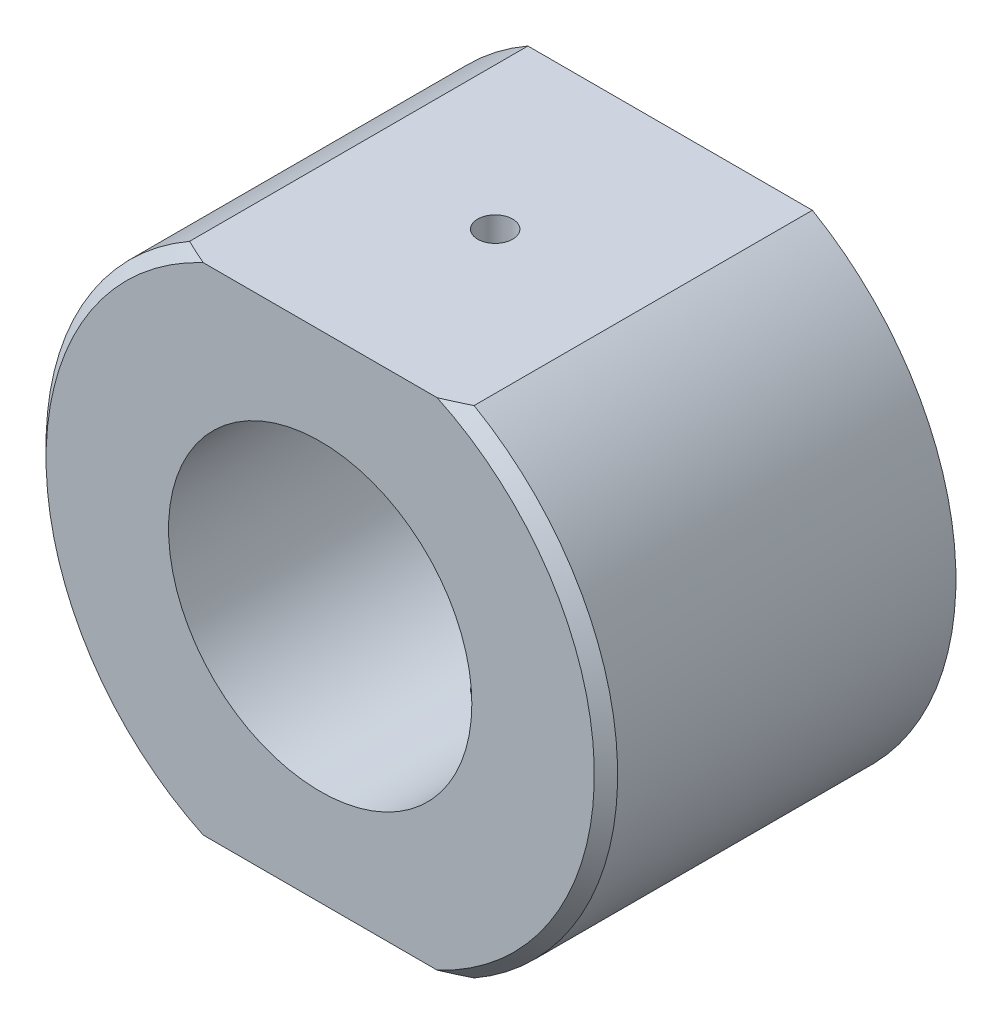
SolidWorks part; units mm, degrees
ref_plane "Front Plane" through (0, 0, 0) normal (0, 0, 1) x (1, 0, 0)
ref_plane "Top Plane" through (0, 0, 0) normal (0, 1, 0) x (1, 0, 0)
ref_plane "Right Plane" through (0, 0, 0) normal (1, 0, 0) x (0, 0, -1)
sketch "Sketch1" plane through (0, 0, 0) normal (0, 0, 1) x (1, 0, 0)
  line L0 (-66.9593, 0) -> (66.624, 0) construction
  line L1 (-24.3875, 42.5) -> (24.3875, 42.5)
  line L3 (24.3875, -42.5) -> (-24.3875, -42.5)
  arc A0 (-24.3875, 42.5) -> (-24.3875, -42.5) centre (0, 0) ccw
  circle A1 centre (0, 0) radius 26
  arc A2 (24.3875, -42.5) -> (24.3875, 42.5) centre (0, 0) ccw
  dimension "D1" = 98
  dimension "D2" = 52
  dimension "D3" = 42.5
extrude "Boss-Extrude1" add sketch "Sketch1" along normal blind 60
chamfer "Chamfer1" distance 2 angle 45 2 edges at (49, 0, 60) (-49, 0, 60)
sketch "Sketch2" plane through (0, 42.5, 0) normal (0, 1, 0) x (1, 0, 0)
  circle A1 centre (0, -30) radius 3
  dimension "D1" = 6
extrude "Cut-Extrude1" cut sketch "Sketch2" against normal through all both and the other way through all
